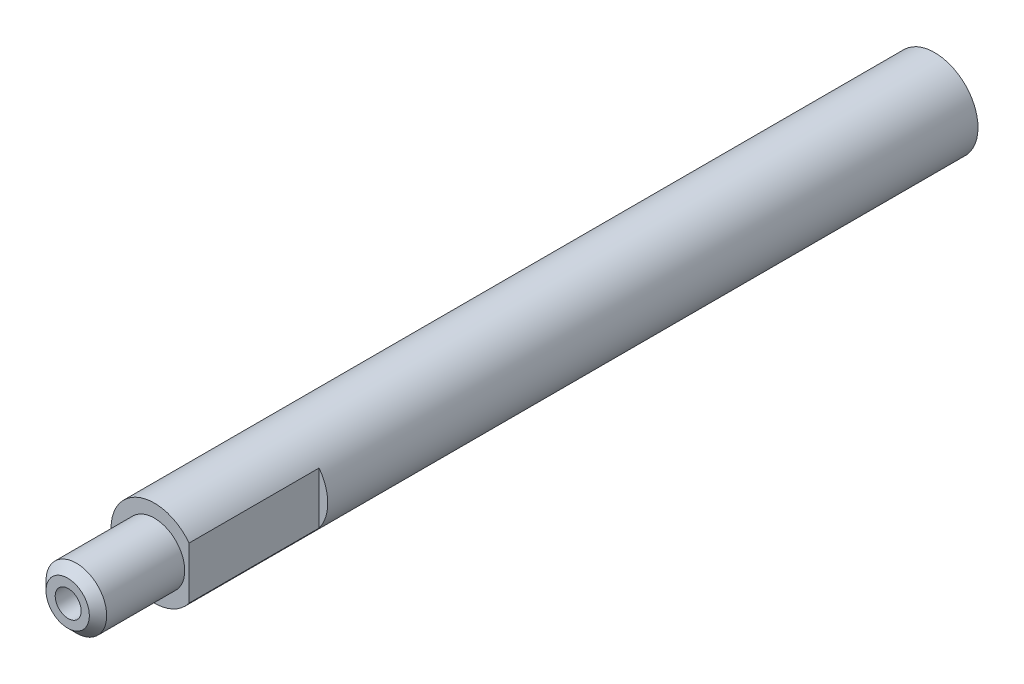
SolidWorks part; units mm, degrees
ref_plane "Front Plane" through (0, 0, 0) normal (0, 0, 1) x (1, 0, 0)
ref_plane "Top Plane" through (0, 0, 0) normal (0, 1, 0) x (1, 0, 0)
ref_plane "Right Plane" through (0, 0, 0) normal (1, 0, 0) x (0, 0, -1)
sketch "Sketch15" plane through (0, 0, 0) normal (0, 0, 1) x (1, 0, 0)
  circle A0 centre (0, 0) radius 5
  dimension "D1" = 10
extrude "Base Extrude" add sketch "Sketch15" along normal blind 100
sketch "Sketch24" plane through (0, 0, 100) normal (0, 0, 1) x (1, 0, 0)
  circle A0 centre (0, 0) radius 3.5
  dimension "D1" = 7
extrude "Front Cut" cut sketch "Sketch24" against normal blind 10 flip side to cut
hole_wizard "Front Hole" positions "3DSketch11" profile "Sketch19" hole size "Ø3.0" standard "ANSI Metric"
sketch3d "3DSketch11"
  point P0 (0.0622, -0.0073, 100)
  point P2 (0, 0, 0)
sketch "Sketch19" plane through (0.0622, -0.0073, 100) normal (1, 0, 0) x (0, -1, 0)
  line L0 (0, 0) -> (0, 10.9013)
  line L1 (0, 10.9013) -> (1.5, 10)
  line L2 (1.5, 10) -> (1.5, 0)
  line L5 (1.5, 0) -> (0, 0)
  line L10 (0, 10.9013) -> (-1.5, 10) construction
  line L11 (0, -6.35) -> (0, 107.95) construction
  dimension "Hole Dia." = 3
  dimension "Hole Depth" = 10
  dimension "Drill Angle" = 118
chamfer "Chamfer1" distance 1 angle 45 1 edges at (3.5, 0, 100)
sketch "Keyway" plane through (0, 0, 100) normal (0, 0, 1) x (1, 0, 0)
  line L0 (4, 3) -> (4, -3)
  circle A0 centre (0, 0) radius 5 construction
  circle A4 centre (0, 0) radius 5
  circle A5 centre (0, 0) radius 2.5
  dimension "D3" = 6
extrude "Keyway-Cut" cut sketch "Keyway" against normal blind 25 contours L0 A4
hole_wizard "Back Hole" positions "3DSketch14" profile "Sketch23" hole size "Ø4.0" standard "ANSI Metric"
sketch3d "3DSketch14"
  point P5 (0, 0, 0)
  point P6 (0, 0, 0)
sketch "Sketch23" plane through (0, 0, 0) normal (1, 0, 0) x (0, 1, 0)
  line L0 (0, 0) -> (0, 11.2017)
  line L1 (0, 11.2017) -> (2, 10)
  line L2 (2, 10) -> (2, 0)
  line L5 (2, 0) -> (0, 0)
  line L10 (0, 11.2017) -> (-2, 10) construction
  line L11 (0, -6.35) -> (0, 107.95) construction
  dimension "Hole Dia." = 4
  dimension "Hole Depth" = 10
  dimension "Drill Angle" = 118
